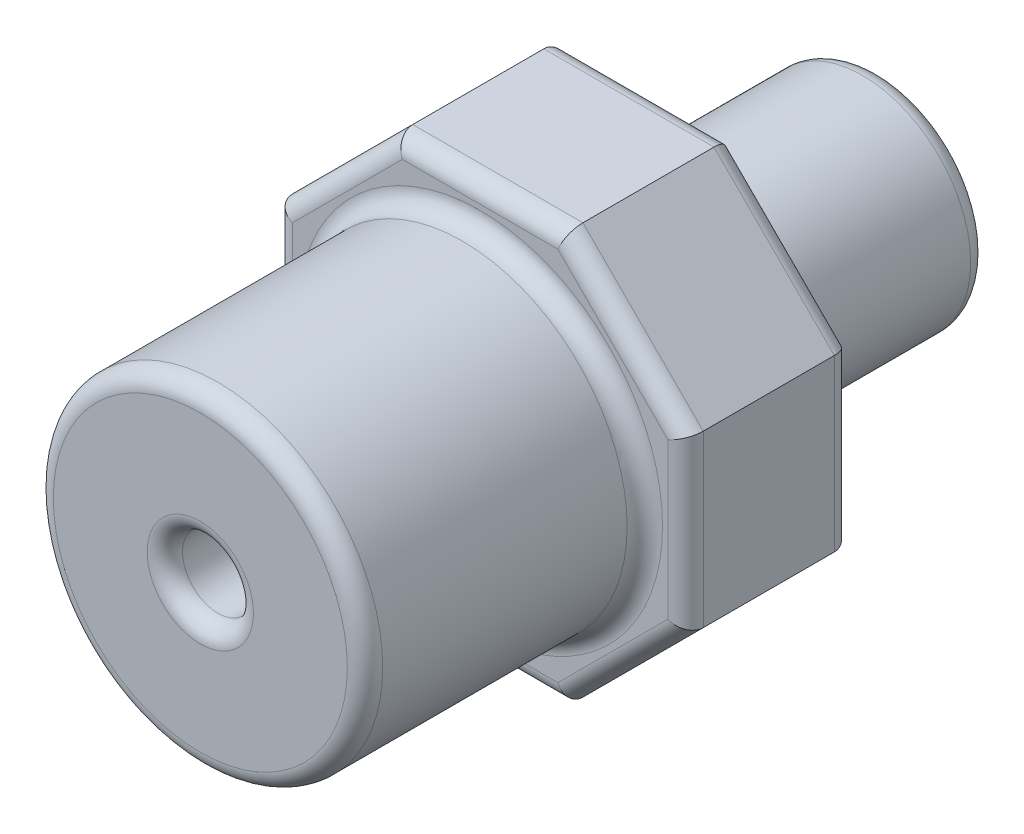
SolidWorks part; units mm, degrees
ref_plane "Front Plane" through (0, 0, 0) normal (0, 0, 1) x (1, 0, 0)
ref_plane "Top Plane" through (0, 0, 0) normal (0, 1, 0) x (1, 0, 0)
ref_plane "Right Plane" through (0, 0, 0) normal (1, 0, 0) x (0, 0, -1)
sketch "Sketch1" plane through (0, 0, 0) normal (0, 0, 1) x (1, 0, 0)
  circle A0 centre (0, 0) radius 3.05
  circle A1 centre (0, 0) radius 1
  dimension "D1" = 6.1
  dimension "D2" = 2
extrude "Boss-Extrude1" add sketch "Sketch1" along normal blind 6.6
sketch "Sketch2" plane through (0, 0, 6.6) normal (0, 0, 1) x (1, 0, 0)
  line L0 (0, 0) -> (4.243, 0) construction
  line L1 (5.8, -2.4024) -> (5.8, 2.4024)
  line L2 (0, 0) -> (0, 1) construction
  line L3 (5.8, 2.4024) -> (2.4024, 5.8)
  line L4 (2.4024, 5.8) -> (-2.4024, 5.8)
  line L5 (2.4024, -5.8) -> (-2.4024, -5.8)
  line L6 (5.8, -2.4024) -> (2.4024, -5.8)
  line L7 (-5.8, -2.4024) -> (-2.4024, -5.8)
  line L8 (-5.8, 2.4024) -> (-2.4024, 5.8)
  line L9 (-5.8, -2.4024) -> (-5.8, 2.4024)
  circle A0 centre (0, 0) radius 1 construction
  circle A1 centre (0, 0) radius 1
  point P6 (5.8, 1.9683)
  point P8 (-5.8, 0)
  point P10 (2.2445, 4.9848)
  point P13 (5.8, 0)
  point P14 (0, 5.8)
  point P17 (0, -5.8)
  dimension "D1" = 11.6
  dimension "D2" = 11.6
extrude "Boss-Extrude2" add sketch "Sketch2" along normal blind 4.7
sketch "Sketch3" plane through (0, 0, 11.3) normal (0, 0, 1) x (1, 0, 0)
  circle A0 centre (0, 0) radius 4.65
  circle A1 centre (0, 0) radius 1 construction
  circle A2 centre (0, 0) radius 1
  dimension "D1" = 9.3
extrude "Boss-Extrude3" add sketch "Sketch3" along normal blind 7.9
fillet "Fillet1" radius 0.5 22 edges at (1, 0, 19.2) (4.65, 0, 19.2) (0, 5.8, 11.3) (4.1012, 4.1012, 11.3) (5.8, 0, 11.3) (4.1012, -4.1012, 11.3) (0, -5.8, 11.3) (-4.1012, -4.1012, 11.3) (-5.8, 0, 11.3) (-4.1012, 4.1012, 11.3) (4.65, 0, 11.3) (-5.8, 0, 6.6) (-4.1012, -4.1012, 6.6) (0, -5.8, 6.6) (4.1012, -4.1012, 6.6) (5.8, 0, 6.6) (4.1012, 4.1012, 6.6) (0, 5.8, 6.6) (-4.1012, 4.1012, 6.6) (1, 0, 0) (3.05, 0, 0) (3.05, 0, 6.6)
